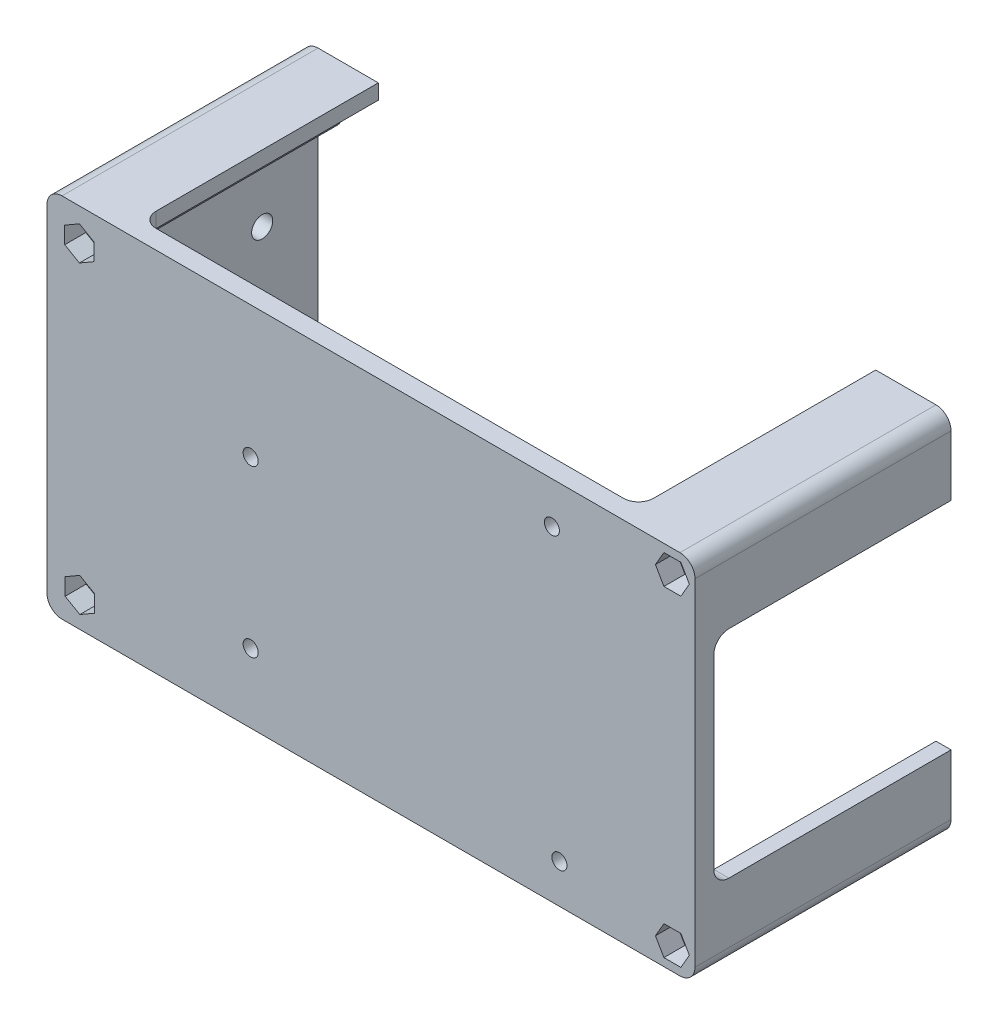
SolidWorks part; units mm, degrees
ref_plane "Front Plane" through (0, 0, 0) normal (0, 0, 1) x (1, 0, 0)
ref_plane "Top Plane" through (0, 0, 0) normal (0, 1, 0) x (1, 0, 0)
ref_plane "Right Plane" through (0, 0, 0) normal (1, 0, 0) x (0, 0, -1)
sketch "Sketch1" plane through (0, 0, 0) normal (0, 0, 1) x (1, 0, 0)
  line L0 (45.7518, 26.4668) -> (45.7518, -26.8732) construction
  line L1 (54.6418, -30.9118) -> (-54.6418, -30.9118)
  line L2 (54.6418, -30.9118) -> (54.6418, 30.9118)
  line L3 (54.6418, 30.9118) -> (-54.6418, 30.9118)
  line L4 (-54.6418, -30.9118) -> (-54.6418, 30.9118)
  line L5 (54.6418, -30.9118) -> (-54.6418, 30.9118) construction
  line L6 (54.6418, 30.9118) -> (-54.6418, -30.9118) construction
  line L7 (45.7518, -26.8732) -> (-17.7482, -26.8732) construction
  line L8 (-17.7482, -26.8732) -> (-17.7482, -21.1582) construction
  line L9 (-17.7482, -21.1582) -> (-20.2882, -18.6182) construction
  line L10 (-20.2882, -18.6182) -> (-20.2882, 14.1478) construction
  line L11 (-20.2882, 14.1478) -> (-17.7482, 16.6878) construction
  line L12 (-17.7482, 16.6878) -> (-17.7482, 26.4668) construction
  line L13 (-17.7482, 26.4668) -> (45.7518, 26.4668) construction
  line L14 (54.6417, 20.0735) -> (54.6418, 8.9535) construction
  line L15 (54.6418, 0) -> (-54.6418, 0) construction
  circle A0 centre (30.5117, 23.9268) radius 1.27
  circle A1 centre (-20.2883, 8.6868) radius 1.27
  circle A2 centre (-20.2883, -19.2532) radius 1.27
  circle A3 centre (31.7817, -24.3332) radius 1.27
  circle A4 centre (50.8317, -27.1018) radius 1.5875
  circle A5 centre (-49.1681, 25.4381) radius 1.5875
  circle A6 centre (-49.1018, -25.8718) radius 1.5875
  circle A7 centre (50.8317, 27.1018) radius 1.5875
  point P0 (0, 0)
  dimension "D12" = 3.175
  dimension "D13" = 3.81
  dimension "D14" = 3.81
  dimension "D19" = 2.54
  dimension "D1" = 109.2835
  dimension "D2" = 61.8236
  dimension "D3" = 50.8
  dimension "D4" = 53.34
  dimension "D5" = 15.24
  dimension "D6" = 2.54
  dimension "D7" = 48.26
  dimension "D8" = 52.07
  dimension "D9" = 27.94
  dimension "D10" = 15.24
  dimension "D11" = 4.445
  dimension "D15" = 5.4737
  dimension "D16" = 5.4737
  dimension "D17" = 5.04
  dimension "D18" = 5.54
  dimension "D20" = 8.89
extrude "Boss-Extrude1" add sketch "Sketch1" along normal blind 3.175
sketch "Sketch3" plane through (0, 0, 0) normal (0, 0, 1) x (1, 0, 0)
  line L1 (-54.6418, 30.9118) -> (-41.9418, 30.9118)
  line L2 (-54.6418, 30.9118) -> (-54.6418, 18.2118)
  line L3 (-54.6418, -30.9118) -> (-41.9418, -30.9118)
  line L4 (54.6418, 30.9118) -> (54.6418, 18.2118)
  line L6 (52.1018, -24.1919) -> (52.1018, -18.2118)
  line L8 (-52.1018, -24.8323) -> (-52.1018, -18.2118)
  line L9 (52.1018, -28.3718) -> (-52.1018, 28.3718) construction
  line L10 (52.1018, 28.3718) -> (-52.1018, -28.3718) construction
  line L11 (47.9218, -28.3718) -> (41.9418, -28.3718)
  line L12 (-41.9418, 28.3718) -> (-41.9418, 30.9118)
  line L13 (46.225, 28.3718) -> (41.9418, 28.3718)
  line L14 (-52.1018, 18.2118) -> (-54.6418, 18.2118) construction
  line L16 (60.1059, 0) -> (-60.1059, 0) construction
  line L17 (-52.1018, -18.2118) -> (-54.6418, -18.2118) construction
  line L18 (-41.9418, -28.3718) -> (-41.9418, -30.9118)
  line L19 (0, -34.003) -> (0, 34.003) construction
  line L20 (41.9418, 28.3718) -> (41.9418, 30.9118)
  line L21 (52.1018, 18.2118) -> (54.6418, 18.2118)
  line L22 (52.1018, -18.2118) -> (54.6418, -18.2118)
  line L23 (41.9418, -28.3718) -> (41.9418, -30.9118)
  line L24 (-52.1018, 18.2118) -> (-52.1018, 24.224)
  line L25 (-52.1018, -18.2118) -> (-52.1018, 18.2118)
  line L26 (-54.6418, -18.2118) -> (-54.6418, -30.9118)
  line L27 (-54.6418, 18.2118) -> (-54.6418, -18.2118)
  line L28 (-41.9418, 28.3718) -> (-47.954, 28.3718)
  line L29 (41.9418, 28.3718) -> (-41.9418, 28.3718) construction
  line L30 (41.9418, 30.9118) -> (54.6418, 30.9118)
  line L31 (-41.9418, 30.9118) -> (41.9418, 30.9118) construction
  line L32 (52.1018, 18.2118) -> (52.1018, 22.4951)
  line L33 (52.1018, -18.2118) -> (52.1018, 18.2118) construction
  line L34 (54.6418, -18.2118) -> (54.6418, -30.9118)
  line L35 (54.6418, 18.2118) -> (54.6418, -18.2118) construction
  line L36 (41.9418, -30.9118) -> (54.6418, -30.9118)
  line L37 (-41.9418, -30.9118) -> (41.9418, -30.9118) construction
  line L38 (-41.9418, -28.3718) -> (-47.1446, -28.3718)
  line L39 (41.9418, -28.3718) -> (-41.9418, -28.3718) construction
  circle A0 centre (-49.1681, 25.4381) radius 1.5875 construction
  circle A1 centre (50.8317, -27.1018) radius 1.5875 construction
  circle A2 centre (50.8317, 27.1018) radius 1.5875 construction
  circle A3 centre (-49.1018, -25.8718) radius 1.5875 construction
  circle A4 centre (50.8317, -27.1018) radius 1.5875
  circle A5 centre (50.8317, 27.1018) radius 1.5875
  circle A6 centre (-49.1681, 25.4381) radius 1.5875
  circle A7 centre (-49.1018, -25.8718) radius 1.5875
  arc A8 (-52.1018, 24.224) -> (-47.954, 28.3718) centre (-49.1681, 25.4381) ccw
  arc A9 (-47.1446, -28.3718) -> (-52.1018, -24.8323) centre (-49.1018, -25.8718) ccw
  arc A10 (52.1018, -24.1919) -> (47.9218, -28.3718) centre (50.8317, -27.1018) ccw
  arc A11 (46.225, 28.3718) -> (52.1018, 22.4951) centre (50.8317, 27.1018) ccw
  point P18 (0, 0)
  dimension "D3" = 6.35
  dimension "D1" = 2.54
  dimension "D2" = 12.7
  dimension "D4" = 12.7
extrude "Boss-Extrude2" add sketch "Sketch3" against normal blind 40.005
sketch "Sketch4" plane through (0, 0, -40.005) normal (0, 0, -1) x (-1, 0, 0)
  line L0 (-53.7417, -28.3718) -> (47.1446, -28.3718) construction
  line L1 (-38.1868, -28.3718) -> (52.1018, -28.3718)
  line L2 (-38.1868, -28.3718) -> (-38.1868, 28.3718)
  line L3 (-38.1868, 28.3718) -> (52.1018, 28.3718)
  line L4 (52.1018, -28.3718) -> (52.1018, 28.3718)
  line L5 (-46.225, 28.3718) -> (-41.9418, 28.3718) construction
  line L6 (52.1018, 24.224) -> (52.1017, -26.9113) construction
extrude "Cut-Extrude1" cut sketch "Sketch4" against normal blind 1.905
fillet "Fillet1" radius 2.54 12 edges at (-54.6418, 30.9118, -18.415) (-54.6418, -30.9118, -18.415) (54.6418, -30.9118, -18.415) (54.6418, 30.9118, -18.415) (47.9218, -28.3718, -20.0025) (52.1018, -24.1919, -20.0025) (-52.1018, -24.8323, -19.05) (-52.1018, 24.224, -19.05) (52.1018, 22.4951, -20.0025) (46.225, 28.3718, -20.0025) (-47.1446, -28.3718, -19.05) (-47.954, 28.3718, -19.05)
sketch "Sketch6" plane through (0, 0, 0) normal (0, 0, 1) x (1, 0, 0)
  line L0 (54.6418, 0) -> (-54.6418, 0) construction
  line L1 (-43.1482, 19.1135) -> (-25.3682, 19.1135) construction
  line L2 (-43.1482, 19.1135) -> (-43.1482, -19.1135) construction
  line L3 (-43.1482, -19.1135) -> (-25.3682, -19.1135) construction
  line L4 (-25.3682, 19.1135) -> (-25.3682, -19.1135) construction
  line L5 (-20.2882, -18.6182) -> (-20.2882, 14.1478) construction
  line L6 (-40.6082, 15.6718) -> (-40.6082, -15.6718) construction
  circle A0 centre (-40.6082, 15.6718) radius 1.27
  circle A1 centre (-40.6082, -15.6718) radius 1.27
  point P4 (-43.1482, 0)
  point P13 (-40.6082, 0)
  dimension "D5" = 2.54
  dimension "D1" = 38.227
  dimension "D2" = 17.78
  dimension "D3" = 5.08
  dimension "D4" = 31.3436
  dimension "D6" = 2.54
extrude "Boss-Extrude3" add sketch "Sketch6" against normal blind 5.08
fillet "Fillet2" radius 2.54 6 edges at (-41.9418, 29.6418, 0) (41.9418, 29.6418, 0) (41.9418, -29.6418, 0) (-41.9418, -29.6418, 0) (53.3718, -18.2118, 0) (53.3718, 18.2118, 0)
sketch "Sketch9" plane through (-54.6418, 0, 0) normal (-1, 0, 0) x (0, 0, 1)
  line L1 (-19.3116, 37.3888) -> (-41.8541, 37.3888) construction
  line L2 (-19.3116, 37.3888) -> (-19.3116, -37.3888) construction
  line L3 (-19.3116, -37.3888) -> (-41.8541, -37.3888) construction
  line L4 (-41.8541, 37.3888) -> (-41.8541, -37.3888) construction
  line L5 (-30.5829, 37.3888) -> (-30.5829, -37.3888) construction
  line L6 (-40.005, 28.3718) -> (-40.005, -28.3718) construction
  line L7 (-14.8666, 2.54) -> (-14.8666, -2.54) construction
  line L8 (-12.9616, 2.54) -> (-12.9616, -2.54)
  line L9 (-16.7716, 2.54) -> (-16.7716, -2.54)
  line L10 (60.1059, 0) -> (-60.1059, 0) construction
  circle A0 centre (-30.5829, 9.525) radius 1.778
  circle A1 centre (-30.5829, -9.525) radius 1.778
  arc A2 (-12.9616, 2.54) -> (-16.7716, 2.54) centre (-14.8666, 2.54) ccw
  arc A3 (-16.7716, -2.54) -> (-12.9616, -2.54) centre (-14.8666, -2.54) ccw
  point P6 (-41.8541, 0)
  point P16 (-14.8666, 0)
  dimension "D6" = 3.556
  dimension "D9" = 8.89
  dimension "D1" = 22.5425
  dimension "D2" = 74.7776
  dimension "D3" = 1.8491
  dimension "D4" = 19.05
  dimension "D5" = 9.525
  dimension "D7" = 2.54
  dimension "D8" = 3.81
extrude "Cut-Extrude4" cut sketch "Sketch9" against normal blind 3.81
sketch "Sketch10" plane through (0, 0, 3.175) normal (0, 0, 1) x (1, 0, 0)
  line L1 (-49.1681, 28.2977) -> (-51.6446, 26.8679)
  line L2 (-51.6446, 26.8679) -> (-51.6446, 24.0083)
  line L3 (-51.6446, 24.0083) -> (-49.1681, 22.5785)
  line L4 (-49.1681, 22.5785) -> (-46.6916, 24.0083)
  line L5 (-46.6916, 24.0083) -> (-46.6916, 26.8679)
  line L6 (-46.6916, 26.8679) -> (-49.1681, 28.2977)
  line L7 (-46.6253, -24.442) -> (-49.1018, -23.0122)
  line L8 (-49.1018, -23.0122) -> (-51.5783, -24.442)
  line L9 (-51.5783, -24.442) -> (-51.5783, -27.3016)
  line L10 (-51.5783, -27.3016) -> (-49.1018, -28.7314)
  line L11 (-49.1018, -28.7314) -> (-46.6253, -27.3016)
  line L12 (-46.6253, -27.3016) -> (-46.6253, -24.442)
  line L13 (47.9721, 27.1018) -> (49.4019, 24.6253)
  line L14 (49.4019, 24.6253) -> (52.2616, 24.6253)
  line L15 (52.2616, 24.6253) -> (53.6914, 27.1018)
  line L16 (53.6914, 27.1018) -> (52.2616, 29.5783)
  line L17 (52.2616, 29.5783) -> (49.4019, 29.5783)
  line L18 (49.4019, 29.5783) -> (47.9721, 27.1018)
  line L19 (49.4019, -24.6253) -> (47.9721, -27.1018)
  line L20 (47.9721, -27.1018) -> (49.4019, -29.5783)
  line L21 (49.4019, -29.5783) -> (52.2616, -29.5783)
  line L22 (52.2616, -29.5783) -> (53.6914, -27.1018)
  line L23 (53.6914, -27.1018) -> (52.2616, -24.6253)
  line L24 (52.2616, -24.6253) -> (49.4019, -24.6253)
  circle A0 centre (-49.1681, 25.4381) radius 2.4765 construction
  circle A1 centre (-49.1018, -25.8718) radius 2.4765 construction
  circle A2 centre (50.8317, 27.1018) radius 2.4765 construction
  circle A3 centre (50.8317, -27.1018) radius 2.4765 construction
  dimension "D1" = 4.953
extrude "Cut-Extrude5" cut sketch "Sketch10" against normal blind 3.556
